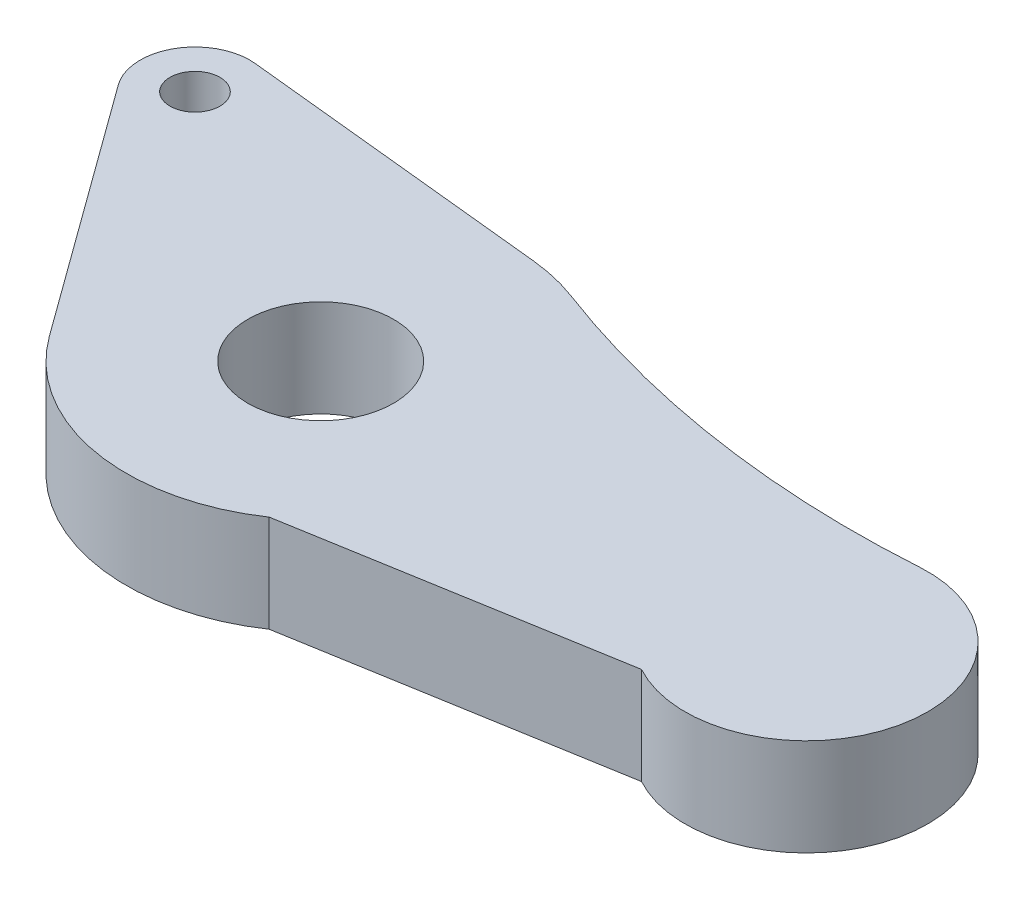
SolidWorks part; units mm, degrees
ref_plane "Front Plane" through (0, 0, 0) normal (0, 0, 1) x (1, 0, 0)
ref_plane "Top Plane" through (0, 0, 0) normal (0, 1, 0) x (1, 0, 0)
ref_plane "Right Plane" through (0, 0, 0) normal (1, 0, 0) x (0, 0, -1)
sketch "Sketch1" plane through (0, 0, 0) normal (0, 1, 0) x (1, 0, 0)
  line L0 (0, 0) -> (10, 0) construction
  line L1 (2.2479, -3.3086) -> (8.7962, -2.1911)
  circle A0 centre (0, 0) radius 1.5
  arc A1 (8.7962, -2.1911) -> (9.8319, 2.4943) centre (10, 0) ccw
  arc A2 (1.4146, 3.7415) -> (2.2479, -3.3086) centre (0, 0) ccw
  arc A3 (1.4146, 3.7415) -> (9.8319, 2.4943) centre (8.4875, 22.4491) ccw
  point P6 (7.0515, 8.0985)
  point P10 (6.7104, 6.8762)
  point P11 (12.8221, 2.1289)
  point P12 (13.1481, 0)
  point P13 (9.3176, 12.7917)
  dimension "D1" = 3
  dimension "D2" = 4
  dimension "D3" = 20
  dimension "D4" = 2.5
  dimension "D5" = 10
extrude "Boss-Extrude1" add sketch "Sketch1" along normal blind 2
sketch "Sketch2" plane through (0, 2, 0) normal (0, 1, 0) x (1, 0, 0)
  line L0 (-5.9841, 4.6353) -> (0.4085, 3.9791)
  line L1 (-7.0134, 2.8476) -> (-3.236, -2.3512)
  circle A0 centre (-6.0995, 3.5116) radius 0.5145
  arc A1 (-5.9841, 4.6353) -> (-7.0134, 2.8476) centre (-6.0995, 3.5116) ccw
  arc A2 (1.4146, 3.7415) -> (2.2479, -3.3086) centre (0, 0) ccw construction
  arc A3 (0.4085, 3.9791) -> (-3.236, -2.3512) centre (0, 0) ccw
extrude "Boss-Extrude2" add sketch "Sketch2" against normal up to surface (2 mm away) up to face at (4.8867, 0, 0.2735)
